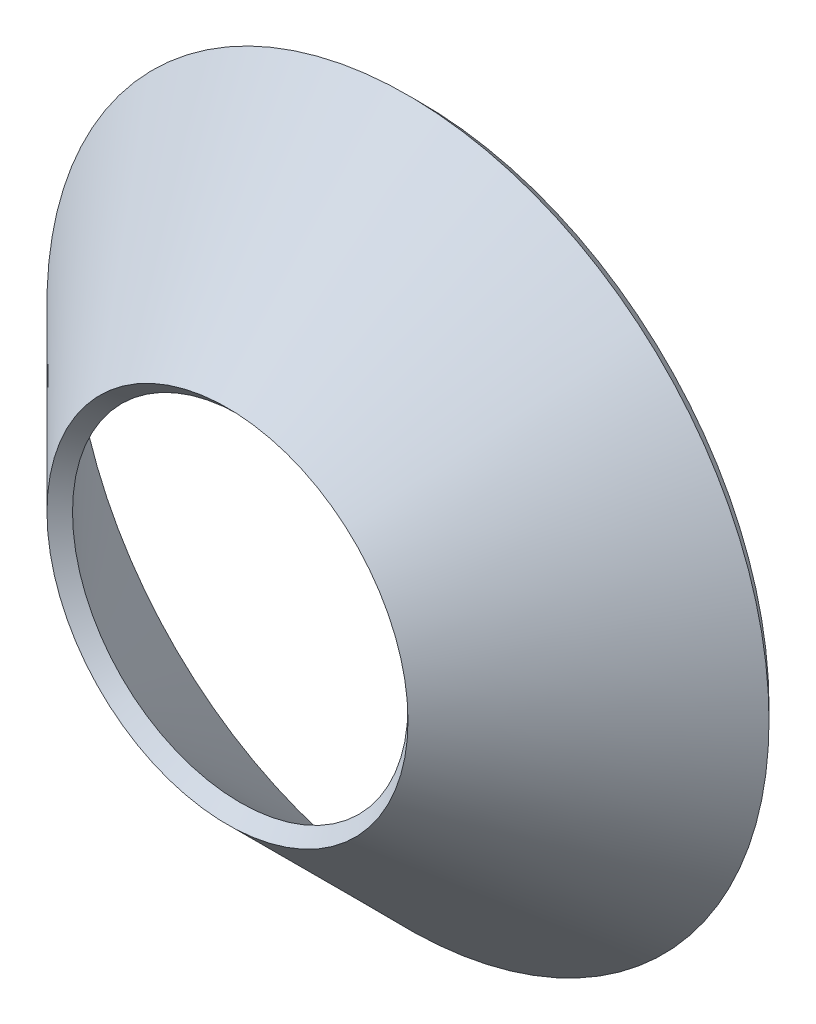
SolidWorks part; units mm, degrees
ref_plane "Front Plane" through (0, 0, 0) normal (1, 0, 0) x (0, 1, 0)
ref_plane "Top Plane" through (0, 0, 0) normal (0, 0, 1) x (0, 1, 0)
ref_plane "Right Plane" through (0, 0, 0) normal (0, 1, 0) x (-1, 0, 0)
sketch "Sketch1" plane through (0, 0, 0) normal (1, 0, 0) x (0, 1, 0)
  line L0 (25.4, 25.4) -> (50.8, 0)
  line L1 (13.8471, 0) -> (-13.8471, 0) construction
  line L2 (0, -13.8471) -> (0, 13.8471) construction
  dimension "D1" = 45
  dimension "D2" = 25.4
  dimension "D3" = 25.4
ref_axis "Axis1" through (0, 0, 26.67) along (0, 0, -1)
revolve "Revolve-Thin1" add sketch "Sketch1" angle 360 about axis through (0, 0, 26.67) along (0, 0, -1)
